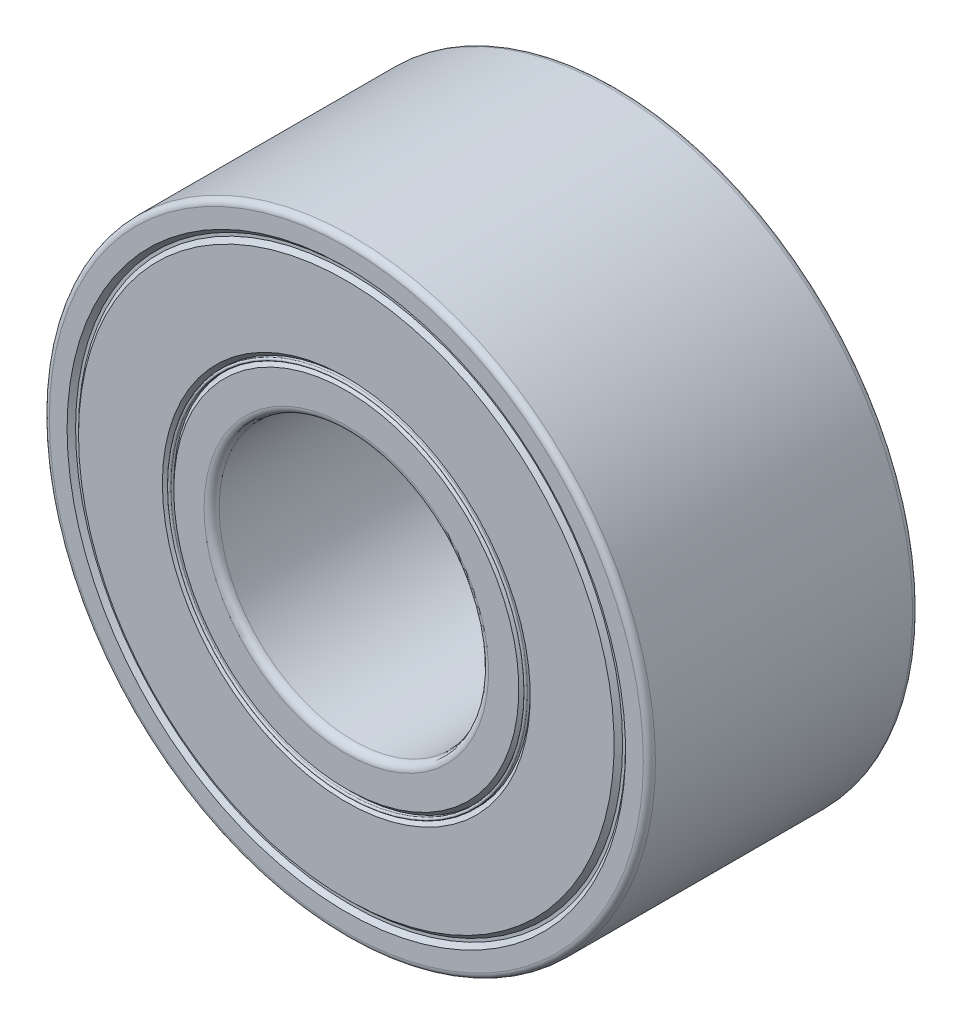
SolidWorks part; units mm, degrees
material "AISI 316 Stainless Steel Sheet (SS)"
ref_plane "Front Plane" through (0, 0, 0) normal (0, 0, 1) x (1, 0, 0)
ref_plane "Top Plane" through (0, 0, 0) normal (0, 1, 0) x (1, 0, 0)
ref_plane "Right Plane" through (0, 0, 0) normal (1, 0, 0) x (0, 0, -1)
sketch "Sketch1" plane through (0, 0, 0) normal (0, 0, 1) x (1, 0, 0)
  line L0 (0, 3.25) -> (0, 4.5) construction
  line L1 (0, 2) -> (0, 3.25) construction
  line L2 (0, 4.5) -> (0, 4.0833) construction
  line L3 (0, 4.0833) -> (0, 3.6667) construction
  line L4 (0, 3.6667) -> (0, 3.25) construction
  circle A0 centre (0, 0) radius 2
  circle A1 centre (0, 0) radius 4.5
  circle A2 centre (0, 0) radius 4.0833 construction
  circle A4 centre (0, 0) radius 2.625 construction
  point P6 (0, 2.625)
  dimension "OD" = 9
  dimension "ID" = 4
sketch "Sketch2" plane through (0, 0, 0) normal (1, 0, 0) x (0, 0, -1)
  line L0 (-2, 4.5) -> (2, 4.5) construction
  line L1 (-2, 2) -> (-2, -2) construction
  line L2 (2, 4.5) -> (2, -4.5) construction
  line L3 (2, 0) -> (-2, 0) construction
  dimension "Width" = 4
  dimension "For Shaft Diameter" = 4
  dimension "For Housing ID" = 9
sketch "Sketch3" plane through (0, 0, 0) normal (1, 0, 0) x (0, 0, -1)
  line L0 (-2, -4.5) -> (2, -4.5)
  line L1 (2, -4.5) -> (2, -4.0833)
  line L2 (2, -4.0833) -> (-2, -4.0833)
  line L3 (-2, -4.0833) -> (-2, -4.5)
  line L4 (-2, 4.5) -> (2, 4.5) construction
  line L6 (-2, -2) -> (2, -2)
  line L9 (-2, -2.625) -> (2, -2.625)
  line L12 (-2, -2.625) -> (-2, -2)
  line L13 (2, -2.625) -> (2, -2)
  line L14 (-2, 0) -> (2, 0) construction
  point P6 (0, -4.0833)
  point P7 (0, -2.625)
  point P8 (0, -2)
  point P20 (0, -4.5)
  dimension "D1" = 1.4583
revolve "Revolve1" add sketch "Sketch3" angle 360 about L3
sketch "Sketch4" plane through (0, 0, 0) normal (1, 0, 0) x (0, 0, -1)
  line L0 (0, 4.5) -> (0, -4.5) construction
  line L1 (-2, -2.625) -> (-2, -4.0833) construction
  circle A0 centre (0, -3.3542) radius 0.875
  point P8 (-2, -3.3542)
  dimension "D1" = 1.75
revolve "Cut-Revolve1" cut sketch "Sketch4" angle 360 about L3
sketch "Sketch5" plane through (0, 0, 0) normal (1, 0, 0) x (0, 0, -1)
  line L0 (0, -2.4792) -> (0, -4.2292)
  line L1 (0, 4.5) -> (0, -4.5) construction
  circle A0 centre (0, -3.3542) radius 0.875 construction
  arc A1 (0, -2.4792) -> (0, -4.2292) centre (0, -3.3542) cw
revolve "Revolve2" add sketch "Sketch5" angle 360 about L0
pattern_circular "CirPattern1" count 9 over 360 about axis through (0, 0, 0) along (0, 0, 1) of bodies 138
fillet "Fillet1" radius 0.09 2 edges at (-4.5, 0, -2) (-4.5, 0, 2)
fillet "Fillet2" radius 0.1125 2 edges at (-2, 0, -2) (-2, 0, 2)
chamfer "Chamfer1" distance 0.063 angle 45 2 edges at (-4.0833, 0, -2) (-4.0833, 0, 2)
chamfer "Chamfer2" distance 0.063 angle 45 2 edges at (-2.625, 0, -2) (-2.625, 0, 2)
sketch "Sketch6" plane through (0, 0, 0) normal (1, 0, 0) x (0, 0, -1)
  line L0 (-2, -2.7318) -> (-2, -3.9766)
  line L1 (-2, -3.9766) -> (-1.937, -4.0396)
  line L2 (-1.937, -4.0396) -> (-1.937, -4.0833)
  line L3 (-2, -2.7318) -> (-1.937, -2.6687)
  line L4 (-1.937, -2.6687) -> (-1.937, -2.625)
  line L5 (-1.937, 4.0833) -> (-1.937, -4.0833) construction
  line L6 (-1.937, -4.0833) -> (-0.875, -4.0833)
  line L7 (-0.875, -4.0833) -> (-0.875, -2.625)
  line L8 (-0.875, -2.625) -> (-1.937, -2.625)
  line L9 (0, 0) -> (0, 4.5) construction
  line L10 (1.937, -4.0833) -> (0.875, -4.0833)
  line L11 (1.937, -4.0396) -> (1.937, -4.0833)
  line L12 (2, -3.9766) -> (1.937, -4.0396)
  line L13 (2, -2.7318) -> (2, -3.9766)
  line L14 (2, -2.7318) -> (1.937, -2.6687)
  line L15 (1.937, -2.6687) -> (1.937, -2.625)
  line L16 (0.875, -2.625) -> (1.937, -2.625)
  line L17 (0.875, -4.0833) -> (0.875, -2.625)
  circle A0 centre (0, -3.3542) radius 0.875 construction
  dimension "D1" = 45
  dimension "D2" = 45
  dimension "D3" = 0.0438
revolve "Revolve3" add sketch "Sketch6" angle 360 about L3
sketch "Sketch7" plane through (0, 0, 0) normal (1, 0, 0) x (0, 0, -1)
  line L0 (-1.937, -2.6687) -> (-1.937, -2.625)
  line L1 (-1.937, -2.625) -> (-1.9781, -2.625)
  line L2 (-1.9781, -2.6687) -> (-1.937, -2.6687)
  line L3 (-2, -2.7318) -> (-2, -2.625) construction
  line L4 (0, 4.5) -> (0, 0) construction
  line L5 (1.937, -2.625) -> (1.9781, -2.625)
  line L6 (1.937, -2.6687) -> (1.937, -2.625)
  line L7 (1.9781, -2.6687) -> (1.937, -2.6687)
  arc A0 (-1.9781, -2.625) -> (-1.9781, -2.6687) centre (-1.9781, -2.6469) ccw
  arc A1 (1.9781, -2.625) -> (1.9781, -2.6687) centre (1.9781, -2.6469) cw
revolve "Revolve4" add sketch "Sketch7" angle 360 about L3
equation "\"D1@Sketch4\"=\"D1@Sketch3\"*1.2"
equation "\"D1@Fillet1\"=\"OD@Sketch1\"*0.01"
equation "\"D1@Fillet2\"=\"D1@Fillet1\"*1.25"
equation "\"D1@Chamfer1\"=\"D1@Fillet1\" * 0.7"
equation "\"D1@Chamfer2\"=\"D1@Chamfer1\""
equation "\"D3@Sketch6\"=\"D1@Sketch3\"*0.03"
equation "\"D1@CirPattern1\"=( pi * \"OD@Sketch1\" )  * .5625 / \"D1@Sketch4\""
